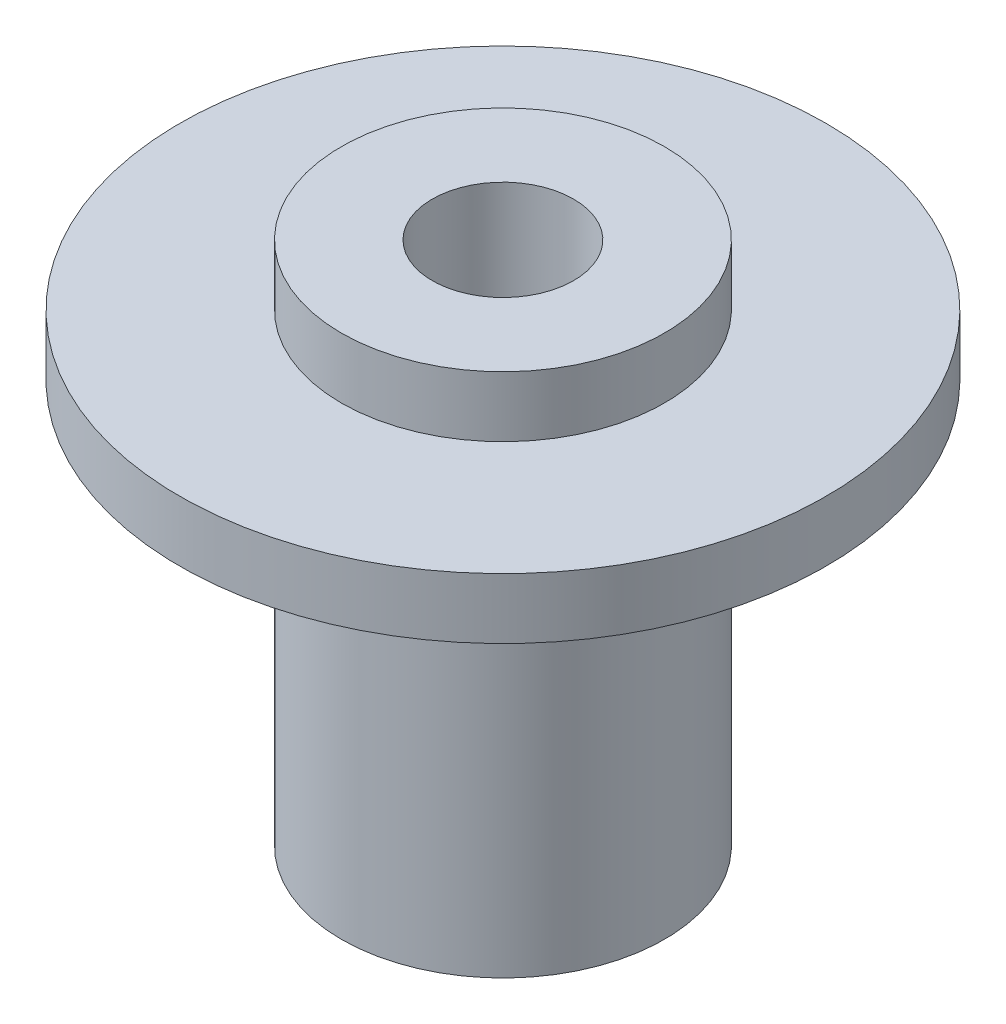
SolidWorks part; units mm, degrees
ref_plane "Front Plane" through (0, 0, 0) normal (0, 0, 1) x (1, 0, 0)
ref_plane "Top Plane" through (0, 0, 0) normal (0, 1, 0) x (1, 0, 0)
ref_plane "Right Plane" through (0, 0, 0) normal (1, 0, 0) x (0, 0, -1)
ref_axis "Axis1" through (0, -55, 0) along (0, 1, 0)
sketch "Sketch2" plane through (0, 0, 0) normal (0, 0, 1) x (1, 0, 0)
  line L0 (0, 0) -> (0, 30)
  line L1 (0, -55) -> (0, 55) construction
  line L2 (0, 30) -> (-80, 30)
  line L3 (-80, 30) -> (-80, 0)
  line L4 (-80, 0) -> (0, 0)
  line L5 (-80, 0) -> (-160, 0)
  line L6 (-160, 0) -> (-160, -30)
  line L7 (-160, -30) -> (0, -30)
  line L8 (0, -30) -> (0, 0)
  line L9 (-80, -30) -> (-80, -230)
  line L10 (-80, -230) -> (0, -230)
  line L11 (0, -230) -> (0, -30)
  line L14 (-25, 0) -> (-80, 0)
  dimension "D1" = 30
  dimension "D2" = 200
  dimension "D3" = 30
  dimension "D4" = 80
revolve "Revolve3" add sketch "Sketch2" angle 360 about axis through (0, -55, 0) along (0, 1, 0)
sketch "Sketch4" plane through (0, 0, 0) normal (0, 0, 1) x (1, 0, 0)
  line L0 (0, -251.4562) -> (0, 53.4087)
  line L1 (0, -55) -> (0, 55) construction
  line L2 (0, 53.4087) -> (-35, 53.4087)
  line L3 (-35, 53.4087) -> (-35, -251.4562)
  line L4 (-35, -251.4562) -> (0, -251.4562)
revolve "Cut-Revolve7" cut sketch "Sketch4" angle 360 about axis through (0, -55, 0) along (0, 1, 0)
